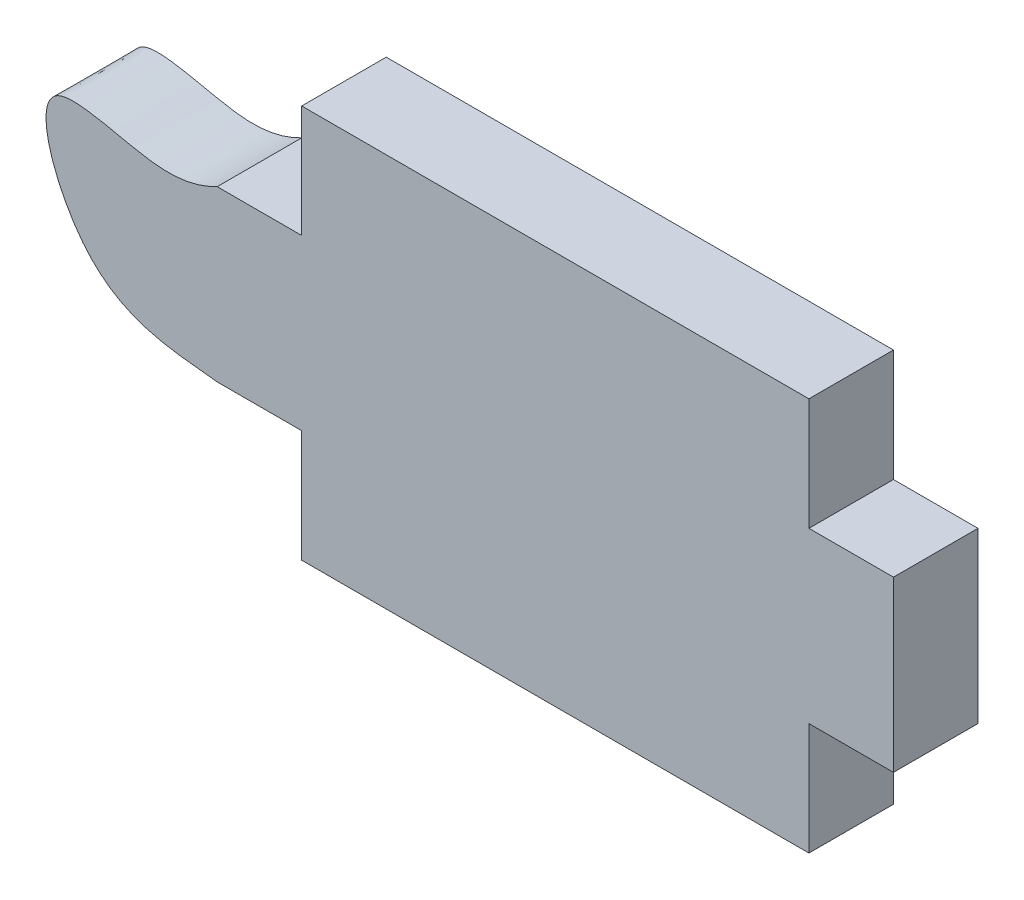
SolidWorks part; units mm, degrees
ref_plane "Front Plane" through (0, 0, 0) normal (0, 0, 1) x (1, 0, 0)
ref_plane "Top Plane" through (0, 0, 0) normal (0, 1, 0) x (1, 0, 0)
ref_plane "Right Plane" through (0, 0, 0) normal (1, 0, 0) x (0, 0, -1)
sketch "Sketch1" plane through (0, 0, 0) normal (0, 0, 1) x (1, 0, 0)
  line L0 (0, 75.5262) -> (0, 71.3134) construction
  line L1 (0, 75.5262) -> (19.05, 75.5262)
  line L3 (0, 60.7507) -> (19.05, 60.7507)
  line L4 (22.225, 71.3134) -> (22.225, 64.9634)
  line L7 (-3.175, 71.3134) -> (0, 71.3134)
  line L8 (0, 75.5262) -> (0, 71.3134)
  line L9 (19.05, 75.5262) -> (19.05, 71.3134) construction
  line L12 (-3.175, 64.9634) -> (0, 64.9634)
  line L13 (0, 60.7507) -> (0, 64.9634)
  line L16 (22.225, 71.3134) -> (19.05, 71.3134)
  line L17 (19.05, 75.5262) -> (19.05, 71.3134)
  line L21 (22.225, 64.9634) -> (19.05, 64.9634)
  line L22 (19.05, 60.7507) -> (19.05, 64.9634)
  spline S0 degree 3 poles (-3.175, 64.9634) (-5.1086, 65.1683) (-8.2668, 65.2888) (-10.4321, 71.6109) (-6.4452, 71.2022) (-4.8811, 70.4406) (-3.175, 71.3134) knots 0 0 0 0 0.353492 0.624795 0.705321 1 1 1 1
  dimension "D1" = 6.35
  dimension "D2" = 6.35
extrude "Boss-Extrude1" add sketch "Sketch1" against normal blind 3.175 contours S0 L7 L8 L1 L17 L16 L4 L21 L22 L3 L13 L12
